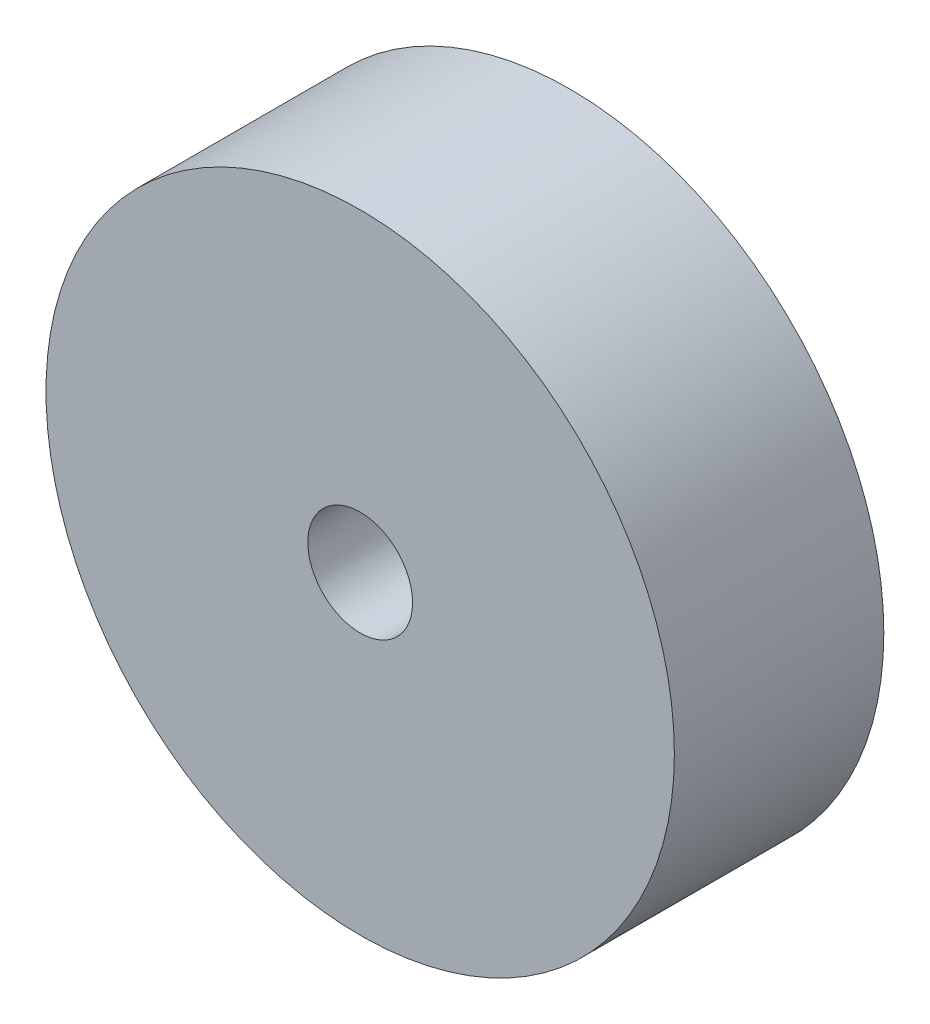
SolidWorks part; units mm, degrees
ref_plane "Front Plane" through (0, 0, 0) normal (0, 0, 1) x (1, 0, 0)
ref_plane "Top Plane" through (0, 0, 0) normal (0, 1, 0) x (1, 0, 0)
ref_plane "Right Plane" through (0, 0, 0) normal (1, 0, 0) x (0, 0, -1)
sketch "Sketch1" plane through (0, 0, 0) normal (0, 0, 1) x (1, 0, 0)
  circle A0 centre (0, 0) radius 19.05
  circle A1 centre (0, 0) radius 3.175
  dimension "D1" = 38.1
  dimension "D2" = 6.35
extrude "Boss-Extrude1" add sketch "Sketch1" along normal blind 12.7
